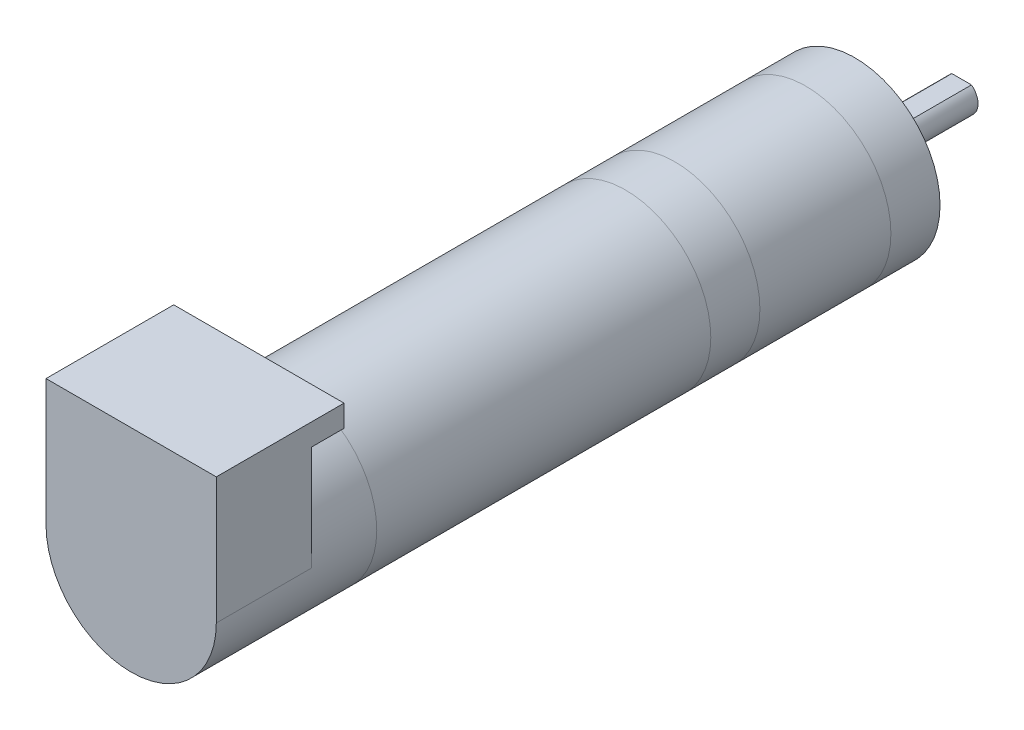
SolidWorks part; units mm, degrees
ref_plane "Plan de face" through (0, 0, 0) normal (0, 0, 1) x (1, 0, 0)
ref_plane "Plan de dessus" through (0, 0, 0) normal (0, 1, 0) x (1, 0, 0)
ref_plane "Plan de droite" through (0, 0, 0) normal (1, 0, 0) x (0, 0, -1)
sketch "Esquisse1" plane through (0, 0, 0) normal (0, 0, 1) x (1, 0, 0)
  circle A0 centre (0, 0) radius 13
  dimension "D1" = 26
extrude "Boss.-Extru.1" add sketch "Esquisse1" along normal blind 7.5
sketch "Esquisse2" plane through (0, 0, 7.5) normal (0, 0, 1) x (1, 0, 0)
  circle A0 centre (0, 0) radius 13
extrude "Boss.-Extru.2" add sketch "Esquisse2" along normal blind 20 separate body
sketch "Esquisse3" plane through (0, 0, 27.5) normal (0, 0, 1) x (1, 0, 0)
  circle A0 centre (0, 0) radius 13
extrude "Boss.-Extru.3" add sketch "Esquisse3" along normal blind 7.5
sketch "Esquisse4" plane through (0, 0, 35) normal (0, 0, 1) x (1, 0, 0)
  circle A0 centre (0, 0) radius 13
extrude "Boss.-Extru.4" add sketch "Esquisse4" along normal blind 51
sketch "Esquisse5" plane through (0, 0, 86) normal (0, 0, 1) x (1, 0, 0)
  circle A0 centre (0, 0) radius 13
extrude "Boss.-Extru.5" add sketch "Esquisse5" along normal blind 10
sketch "Esquisse6" plane through (0, 0, 96) normal (0, 0, 1) x (1, 0, 0)
  line L0 (-13, 0) -> (-13, 19.3215)
  line L1 (-13, 19.3215) -> (13, 19.3215)
  line L2 (13, 19.3215) -> (13, 0)
  arc A0 (-13, 0) -> (13, 0) centre (0, 0) ccw
extrude "Boss.-Extru.6" add sketch "Esquisse6" along normal blind 14.5
sketch "Esquisse7" plane through (0, 0, 96) normal (0, 0, -1) x (-1, 0, 0)
  line L1 (-13, 15.9911) -> (13, 15.9911)
  line L2 (-13, 15.9911) -> (-13, 19.3215)
  line L3 (-13, 19.3215) -> (13, 19.3215)
  line L4 (13, 15.9911) -> (13, 19.3215)
  line L5 (-13, 15.9911) -> (13, 19.3215) construction
  line L6 (-13, 19.3215) -> (13, 15.9911) construction
  point P0 (0, 17.6563)
extrude "Boss.-Extru.7" add sketch "Esquisse7" along normal blind 5
sketch "Esquisse10" plane through (0, 0, 0) normal (0, 0, -1) x (-1, 0, 0)
  circle A0 centre (0, 0) radius 7
  dimension "D1" = 14
extrude "Boss.-Extru.8" add sketch "Esquisse10" along normal blind 2
sketch "Esquisse11" plane through (0, 0, -2) normal (0, 0, -1) x (-1, 0, 0)
  circle A0 centre (0, 0) radius 4
  dimension "D1" = 8
extrude "Boss.-Extru.9" add sketch "Esquisse11" along normal blind 2.5
sketch "Esquisse12" plane through (0, 0, -4.5) normal (0, 0, -1) x (-1, 0, 0)
  line L0 (-1.5, 2) -> (1.5, 2)
  arc A0 (-1.5, 2) -> (1.5, 2) centre (0, 0) ccw
  dimension "D1" = 5
  dimension "D2" = 2
extrude "Boss.-Extru.10" add sketch "Esquisse12" along normal blind 11.8
sketch "Esquisse13" plane through (0, 0, 110.5) normal (0, 0, 1) x (1, 0, 0)
  line L0 (0, 19.3215) -> (0, -13.2991) construction
  line L1 (13, 19.3215) -> (-13, 19.3215) construction
